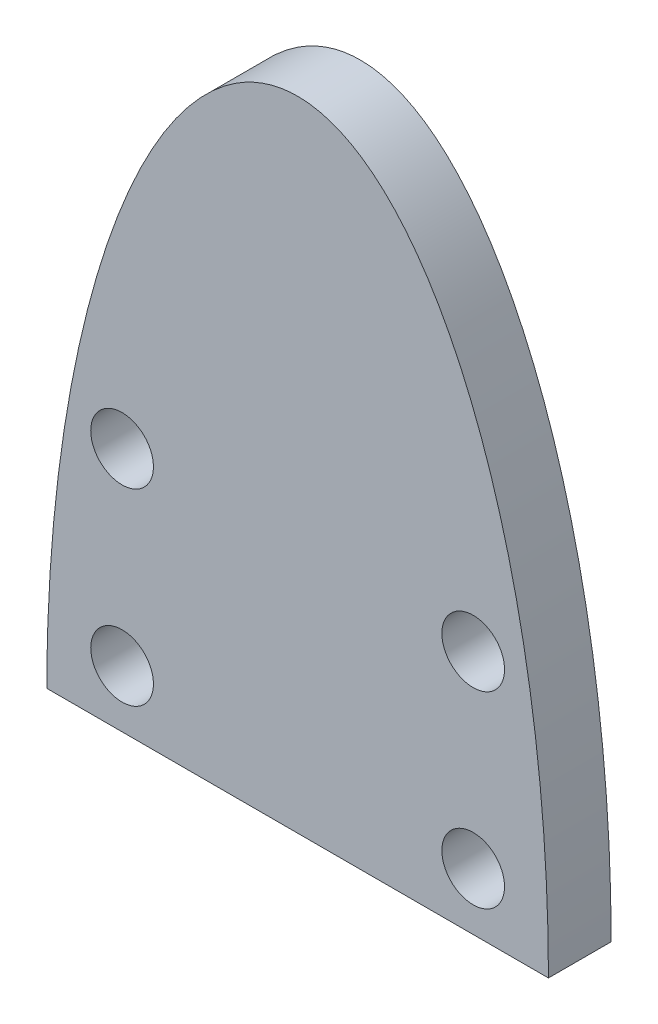
SolidWorks part; units mm, degrees
ref_plane "Front Plane" through (0, 0, 0) normal (0, 0, 1) x (1, 0, 0)
ref_plane "Top Plane" through (0, 0, 0) normal (0, 1, 0) x (1, 0, 0)
ref_plane "Right Plane" through (0, 0, 0) normal (1, 0, 0) x (0, 0, -1)
sketch "Sketch1" plane through (0, 0, 0) normal (0, 0, 1) x (1, 0, 0)
  line L0 (0, 0) -> (101.6, 0)
  ellipse E0 centre (50.8, 0) end of major axis (50.8, 129.286) minor radius 50.8 (101.6, 0) -> (0, 0) ccw
  dimension "D1" = 101.6
  dimension "D2" = 129.286
extrude "Boss-Extrude1" add sketch "Sketch1" along normal blind 12.7 contours E0 L0
sketch "Sketch2" plane through (0, 0, 0) normal (0, 0, -1) x (-1, 0, 0)
  line L0 (-50.8, 0) -> (-50.8, 181.515) construction
  line L1 (0, 0) -> (-101.6, 0) construction
  circle A0 centre (-86.36, 49.6629) radius 6.35
  circle A1 centre (-86.36, 11.5629) radius 6.35
  circle A2 centre (-15.24, 49.6629) radius 6.35
  circle A3 centre (-15.24, 11.5629) radius 6.35
  point P8 (0, 0)
  point P9 (0, 0)
  dimension "D1" = 12.7
  dimension "D2" = 38.1
  dimension "D3" = 35.56
  dimension "D4" = 35.56
extrude "Cut-Extrude1" cut sketch "Sketch2" against normal blind 12.7
